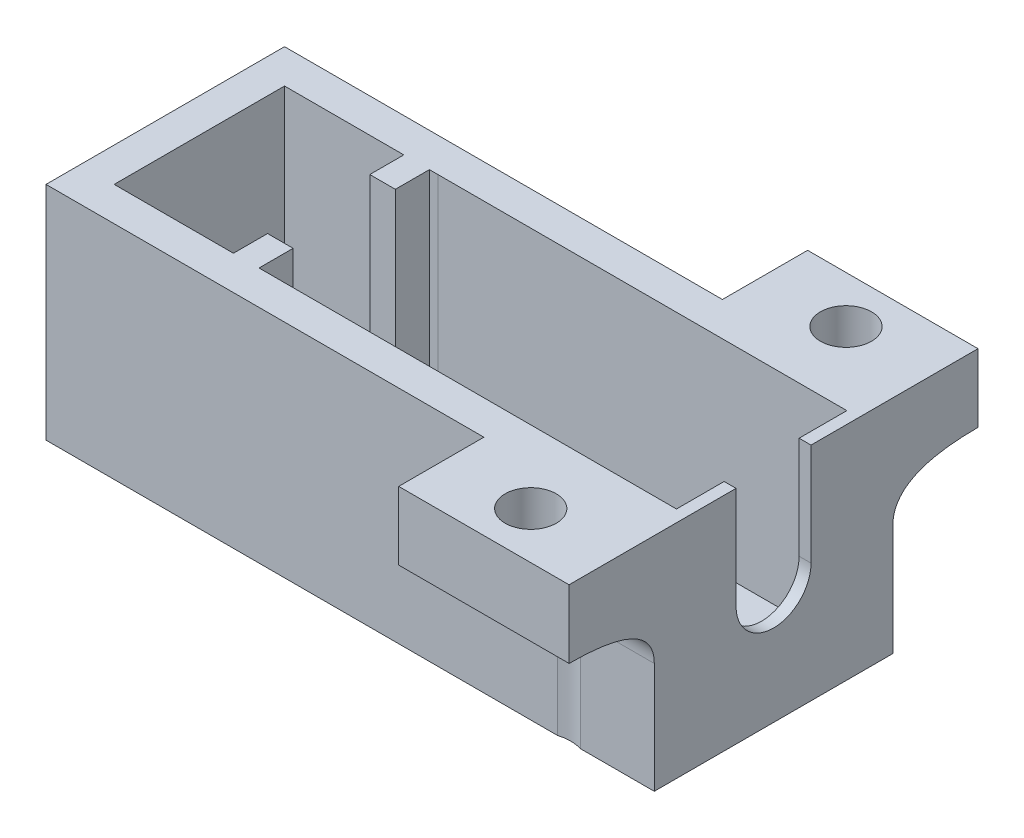
SolidWorks part; units mm, degrees
ref_plane "Front Plane" through (0, 0, 0) normal (0, 0, 1) x (1, 0, 0)
ref_plane "Top Plane" through (0, 0, 0) normal (0, 1, 0) x (1, 0, 0)
ref_plane "Right Plane" through (0, 0, 0) normal (1, 0, 0) x (0, 0, -1)
sketch "Sketch1" plane through (0, 0, 0) normal (0, 1, 0) x (1, 0, 0)
  line L0 (4.8642, 14.8613) -> (4.8642, -1.1387) construction
  line L5 (-7.9858, 14.8613) -> (17.7142, 14.8613)
  line L6 (-7.9858, 14.8613) -> (-7.9858, -1.1387)
  line L7 (-7.9858, -1.1387) -> (17.7142, -1.1387)
  line L8 (17.7142, 14.8613) -> (17.7142, -1.1387)
  line L9 (17.7142, 6.8613) -> (17.0142, 6.8613) construction
  line L10 (17.0142, 6.8613) -> (17.0142, 1.8412) construction
  line L11 (17.0142, 1.8412) -> (17.0142, 11.8412) construction
  line L12 (17.0142, 11.8412) -> (-6.9858, 11.8412) construction
  line L13 (-6.9858, 11.8412) -> (-6.9858, 1.8412) construction
  line L14 (-6.9858, 1.8412) -> (17.0142, 1.8412) construction
  line L16 (-6.9858, 11.8412) -> (17.0142, 11.8412)
  line L17 (-6.9858, 11.8412) -> (-6.9858, 1.8412)
  line L18 (-6.9858, 1.8412) -> (17.0142, 1.8412)
  line L19 (17.0142, 11.8412) -> (17.0142, 1.8412)
extrude "Boss-Extrude5" add sketch "Sketch1" along normal blind 13 contours L6 L5 L8 L7
sketch "Sketch3" plane through (0, 13, 0) normal (0, 1, 0) x (1, 0, 0)
  line L0 (17.7142, 6.8613) -> (17.0154, 6.8613) construction
  line L1 (17.7142, 14.8613) -> (17.7142, -1.1387) construction
  line L2 (17.0154, 6.8613) -> (17.0154, 11.6238) construction
  line L3 (17.0154, 11.6238) -> (17.0154, 1.6238) construction
  line L4 (17.0154, 1.6238) -> (-6.9846, 1.6238) construction
  line L5 (-6.9846, 1.6238) -> (-6.9846, 11.6238) construction
  line L6 (-6.9846, 11.6238) -> (17.0154, 11.6238) construction
  line L8 (-6.9846, 11.6238) -> (17.0154, 11.6238)
  line L9 (-6.9846, 11.6238) -> (-6.9846, 1.6238)
  line L10 (-6.9846, 1.6238) -> (17.0154, 1.6238)
  line L11 (17.0154, 11.6238) -> (17.0154, 1.6238)
extrude "Cut-Extrude1" cut sketch "Sketch3" against normal blind 12
sketch "Sketch6" plane through (-7.9858, 0, 0) normal (-1, 0, 0) x (0, 0, 1)
  line L0 (-6.8613, 13) -> (-6.8613, 0) construction
  line L1 (-14.8613, 13) -> (1.1387, 13) construction
  line L2 (-14.8613, 0) -> (1.1387, 0) construction
  line L3 (-6.8613, 0) -> (-6.8613, 6.5) construction
  line L4 (-6.8613, 13) -> (-9.8613, 13) construction
  line L5 (-9.8613, 13) -> (-9.8613, 1) construction
  line L7 (-9.8613, 13) -> (-3.8613, 13)
  line L8 (-9.8613, 13) -> (-9.8613, 1)
  line L9 (-9.8613, 1) -> (-3.8613, 1)
  line L10 (-3.8613, 13) -> (-3.8613, 1)
extrude "Cut-Extrude6" cut sketch "Sketch6" against normal blind 12
sketch "Sketch12" plane through (0, 0, -14.8613) normal (0, 0, -1) x (-1, 0, 0)
  line L0 (7.9858, 13) -> (7.9858, 0) construction
  line L1 (-17.7142, 13) -> (7.9858, 13)
  line L2 (-17.7142, 13) -> (-17.7142, 0)
  line L3 (-17.7142, 0) -> (7.9858, 0)
  line L4 (7.9858, 13) -> (7.9858, 0)
extrude "Cut-Extrude9" cut sketch "Sketch12" against normal blind 1
sketch "Sketch13" plane through (0, 0, 1.1387) normal (0, 0, 1) x (1, 0, 0)
  line L1 (-7.9858, 13) -> (17.7142, 13)
  line L2 (-7.9858, 13) -> (-7.9858, 0)
  line L3 (-7.9858, 0) -> (17.7142, 0)
  line L4 (17.7142, 13) -> (17.7142, 0)
extrude "Cut-Extrude10" cut sketch "Sketch13" against normal blind 1
sketch "Sketch14" plane through (0, 13, 0) normal (0, 1, 0) x (1, 0, 0)
  line L0 (17.7142, 13.8613) -> (17.7142, -0.1387) construction
  line L1 (-7.9858, 13.8613) -> (17.7142, 13.8613)
  line L2 (-7.9858, 13.8613) -> (-7.9858, 13.6213)
  line L3 (-7.9858, 13.6213) -> (17.7142, 13.6213)
  line L4 (17.7142, 13.8613) -> (17.7142, 13.6213)
extrude "Cut-Extrude11" cut sketch "Sketch14" against normal through all
sketch "Sketch15" plane through (0, 13, 0) normal (0, 1, 0) x (1, 0, 0)
  line L3 (-7.9858, -0.1387) -> (17.7142, -0.1387)
  line L4 (-7.9858, -0.1387) -> (-7.9858, -0.3787)
  line L5 (-7.9858, -0.3787) -> (17.7142, -0.3787)
  line L6 (17.7142, -0.1387) -> (17.7142, -0.3787)
extrude "Boss-Extrude6" add sketch "Sketch15" against normal blind 13
sketch "Sketch17" plane through (17.7142, 0, 0) normal (1, 0, 0) x (0, 0, -1)
  line L0 (13.6213, 13) -> (18.6213, 13)
  line L1 (18.6213, 13) -> (18.6213, 9)
  line L2 (-0.3787, 13) -> (-5.3787, 13)
  line L3 (-5.3787, 13) -> (-5.3787, 9)
  line L4 (18.6213, 9) -> (13.6213, 9) construction
  line L5 (13.6213, 0) -> (13.6213, 13) construction
  line L6 (13.6213, 9) -> (13.6213, 6.5) construction
  line L7 (-5.3787, 9) -> (-0.3787, 9) construction
  line L8 (-0.3787, 0) -> (-0.3787, 13) construction
  line L9 (-0.3787, 9) -> (-0.3787, 6.5) construction
  line L10 (-0.3787, 13) -> (-0.3787, 6.5)
  line L11 (13.6213, 13) -> (13.6213, 6.5)
  spline S0 degree 2 poles (18.6213, 9) (13.6213, 9) (13.6213, 6.5) knots 0 0 0 1 1 1
  spline S1 degree 2 poles (-5.3787, 9) (-0.3787, 9) (-0.3787, 6.5) knots 0 0 0 1 1 1
extrude "Boss-Extrude8" add sketch "Sketch17" against normal blind 10
sketch "Sketch19" plane through (0, 13, 0) normal (0, 1, 0) x (1, 0, 0)
  line L0 (12.7142, 18.6213) -> (12.7142, 15.8713) construction
  line L1 (7.7142, 18.6213) -> (17.7142, 18.6213) construction
  line L2 (12.7142, -5.3787) -> (12.7142, -2.6287) construction
  line L3 (7.7142, -5.3787) -> (17.7142, -5.3787) construction
  circle A0 centre (12.7142, 15.8713) radius 2.35
  circle A1 centre (12.7142, -2.6287) radius 2.35
extrude "Cut-Extrude12" cut sketch "Sketch19" against normal through all
sketch "Sketch20" plane through (0, 13, 0) normal (0, 1, 0) x (1, 0, 0)
  line L0 (12.7142, 18.6213) -> (12.7142, 15.8713) construction
  line L1 (7.7142, 18.6213) -> (17.7142, 18.6213) construction
  line L2 (12.7142, -5.3787) -> (12.7142, -2.6287) construction
  line L3 (7.7142, -5.3787) -> (17.7142, -5.3787) construction
  circle A0 centre (12.7142, 15.8713) radius 2.4
  circle A1 centre (12.7142, -2.6287) radius 2.45
extrude "Boss-Extrude9" add sketch "Sketch20" against normal blind 2.5
sketch "Sketch21" plane through (0, 13, 0) normal (0, 1, 0) x (1, 0, 0)
  line L0 (12.7142, -5.3787) -> (12.7142, -2.6287) construction
  line L1 (7.7142, -5.3787) -> (17.7142, -5.3787) construction
  line L2 (12.7142, 18.6213) -> (12.7142, 15.8713) construction
  line L3 (7.7142, 18.6213) -> (17.7142, 18.6213) construction
  circle A0 centre (12.7142, 15.8713) radius 1.5
  circle A1 centre (12.7142, -2.6287) radius 1.5
extrude "Cut-Extrude13" cut sketch "Sketch21" against normal through all
sketch "Sketch22" plane through (0, 13, 0) normal (0, 1, 0) x (1, 0, 0)
  line L1 (-7.9858, -0.3787) -> (-17.9858, -0.3787)
  line L2 (-7.9858, -0.3787) -> (-7.9858, 13.6213)
  line L3 (-7.9858, 13.6213) -> (-17.9858, 13.6213)
  line L4 (-17.9858, -0.3787) -> (-17.9858, 13.6213)
extrude "Boss-Extrude11" add sketch "Sketch22" against normal blind 13
sketch "Sketch25" plane through (0, 13, 0) normal (0, 1, 0) x (1, 0, 0)
  line L0 (-17.9858, 13.6213) -> (-17.9858, 11.6213) construction
  line L1 (-17.9858, 13.6213) -> (-17.9858, -0.3787) construction
  line L2 (-17.9858, 11.6213) -> (-17.9858, 1.6213) construction
  line L3 (-17.9858, 11.6213) -> (-15.9858, 11.6213) construction
  line L5 (-15.9858, 11.6213) -> (-7.9858, 11.6213)
  line L6 (-15.9858, 11.6213) -> (-15.9858, 1.6213)
  line L7 (-15.9858, 1.6213) -> (-7.9858, 1.6213)
  line L8 (-7.9858, 11.6213) -> (-7.9858, 1.6213)
extrude "Cut-Extrude17" cut sketch "Sketch25" against normal blind 12
sketch "Sketch26" plane through (0, 13, 0) normal (0, 1, 0) x (1, 0, 0)
  line L5 (-6.9846, 1.6238) -> (-7.4846, 1.6238) construction
  line L6 (-6.9846, 11.6238) -> (-7.4846, 11.6238) construction
  line L7 (-7.4846, 1.6238) -> (-8.9846, 1.6238)
  line L8 (-7.4846, 1.6238) -> (-7.4846, 3.6238)
  line L9 (-7.4846, 3.6238) -> (-8.9846, 3.6238)
  line L10 (-8.9846, 1.6238) -> (-8.9846, 3.6238)
  line L12 (-7.4846, 11.6238) -> (-8.9846, 11.6238)
  line L13 (-7.4846, 11.6238) -> (-7.4846, 9.6238)
  line L14 (-7.4846, 9.6238) -> (-8.9846, 9.6238)
  line L15 (-8.9846, 11.6238) -> (-8.9846, 9.6238)
extrude "Boss-Extrude12" add sketch "Sketch26" against normal blind 13
sketch "Sketch27" plane through (0, 13, 0) normal (0, 1, 0) x (1, 0, 0)
  line L1 (-6.9846, 9.8613) -> (-7.4846, 9.8613)
  line L2 (-6.9846, 9.8613) -> (-6.9846, 11.6213)
  line L3 (-6.9846, 11.6213) -> (-7.4846, 11.6213)
  line L4 (-7.4846, 9.8613) -> (-7.4846, 11.6213)
  line L5 (-7.9858, 3.6238) -> (-6.9846, 3.6238)
  line L6 (-7.9858, 3.6238) -> (-7.9858, 3.8613)
  line L7 (-7.9858, 3.8613) -> (-6.9846, 3.8613)
  line L8 (-6.9846, 3.6238) -> (-6.9846, 3.8613)
  line L9 (-6.9846, 1.6238) -> (-7.4852, 1.6238)
  line L10 (-6.9846, 1.6238) -> (-6.9846, 3.6238)
  line L11 (-6.9846, 3.6238) -> (-7.4852, 3.6238)
  line L12 (-7.4852, 1.6238) -> (-7.4852, 3.6238)
  line M9 (-7.4846, 9.8613) -> (-6.9846, 9.8613)
  line M10 (-6.9846, 9.8613) -> (-6.9846, 11.6238)
  line M26 (-6.9846, 1.6238) -> (-6.9846, 3.8613)
extrude "Cut-Extrude18" cut sketch "Sketch27" against normal blind 12 contours L12 L9 L5 M26 | L4 L3 M9 M10
sketch "Sketch28" plane through (0, 13, 0) normal (0, 1, 0) x (1, 0, 0)
  line L0 (-8.9846, 3.6238) -> (-8.9846, 1.6238) construction
  line L1 (-8.9846, 1.8186) -> (-7.7072, 1.8186)
  line L2 (-8.9846, 1.8186) -> (-8.9846, 0.9578)
  line L3 (-8.9846, 0.9578) -> (-7.7072, 0.9578)
  line L4 (-7.7072, 1.8186) -> (-7.7072, 0.9578)
extrude "Boss-Extrude13" add sketch "Sketch28" against normal blind 12
sketch "Sketch35" plane through (17.7142, 0, 0) normal (1, 0, 0) x (0, 0, -1)
  line L0 (18.6213, 13) -> (6.6213, 13) construction
  line L2 (18.6213, 13) -> (-5.3787, 13) construction
  line L3 (6.6213, 13) -> (6.6213, 7) construction
  line L4 (4.4214, 7) -> (4.4214, 13)
  line L5 (4.4214, 13) -> (8.8212, 13)
  line L6 (8.8212, 13) -> (8.8212, 7)
  arc A0 (8.8212, 7) -> (4.4214, 7) centre (6.6213, 7) cw
extrude "Cut-Extrude20" cut sketch "Sketch35" against normal blind 12
